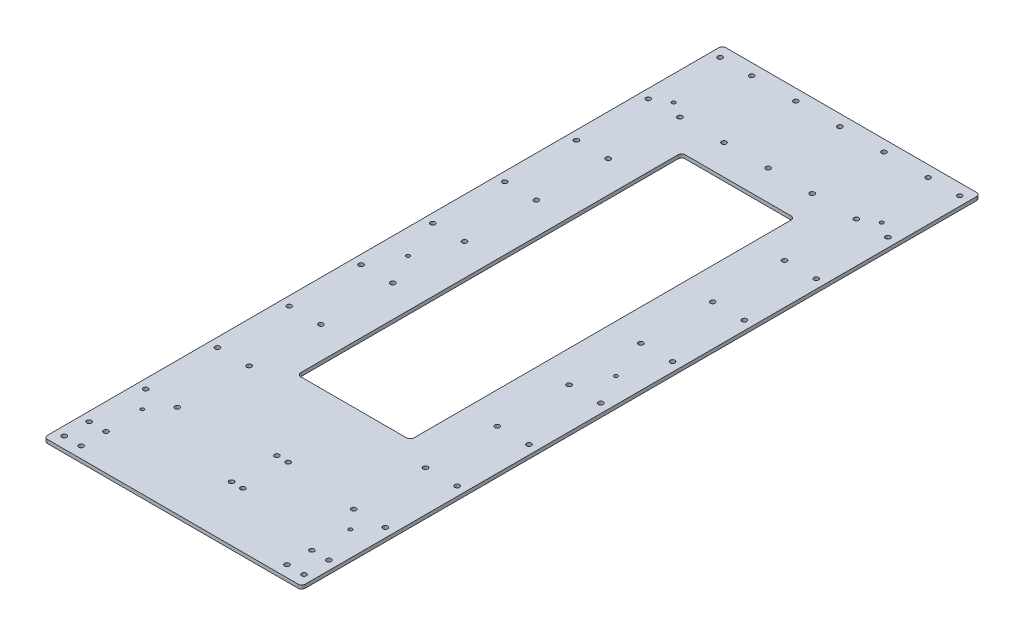
SolidWorks part; units mm, degrees
ref_plane "Front Plane" through (0, 0, 0) normal (0, 0, 1) x (1, 0, 0)
ref_plane "Top Plane" through (0, 0, 0) normal (0, 1, 0) x (1, 0, 0)
ref_plane "Right Plane" through (0, 0, 0) normal (1, 0, 0) x (0, 0, -1)
sketch "Sketch1" plane through (0, 0, 0) normal (0, 1, 0) x (1, 0, 0)
  line L0 (92, 300) -> (92, -300) construction
  line L1 (-114, -300) -> (114, -300)
  line L2 (-114, -300) -> (-114, 300)
  line L3 (-114, 300) -> (114, 300)
  line L4 (114, -300) -> (114, 300)
  line L5 (-114, -300) -> (114, 300) construction
  line L6 (-114, 300) -> (114, -300) construction
  line L7 (-114, 0) -> (114, 0) construction
  line L8 (0, 300) -> (0, -300) construction
  line L9 (78, 290) -> (50, 290) construction
  line L10 (72.9634, -279) -> (112.2482, -279) construction
  line L11 (-50, -140) -> (50, -140)
  line L12 (-50, -140) -> (-50, 200)
  line L13 (-50, 200) -> (50, 200)
  line L14 (50, -140) -> (50, 200)
  line L15 (-24, -231) -> (28.6506, -231) construction
  circle A0 centre (106, 290) radius 2.1
  circle A10 centre (106, -290) radius 2.1
  circle A11 centre (78, -290) radius 2.1 construction
  circle A21 centre (78, 290) radius 2.1
  circle A22 centre (92, 0) radius 1.6
  circle A23 centre (92, 235) radius 1.6
  circle A24 centre (92, -235) radius 1.6
  circle A34 centre (-92, -235) radius 1.6
  circle A42 centre (-78, -290) radius 2.1 construction
  circle A43 centre (-106, -290) radius 2.1
  circle A62 centre (91, -290) radius 2.1
  circle A63 centre (91, -268) radius 2.1
  circle A64 centre (106, -268) radius 2.1
  circle A65 centre (-91, -290) radius 2.1
  circle A66 centre (-106, -268) radius 2.1
  circle A67 centre (-91, -268) radius 2.1
  circle A68 centre (13, -251) radius 2.1
  circle A69 centre (3, -251) radius 2.1
  circle A70 centre (13, -211) radius 2.1
  circle A71 centre (3, -211) radius 2.1
  circle A72 centre (-39, 290) radius 2.1
  circle A73 centre (-39, 226.5) radius 2.1
  circle A74 centre (106, -232) radius 2.1 [skipped]
  circle A75 centre (106, -174) radius 2.1 [skipped]
  circle A76 centre (106, -116) radius 2.1 [skipped]
  circle A77 centre (106, -58) radius 2.1 [skipped]
  circle A78 centre (106, 0) radius 2.1 [skipped]
  circle A79 centre (106, 58) radius 2.1 [skipped]
  circle A80 centre (106, 116) radius 2.1 [skipped]
  circle A81 centre (106, 174) radius 2.1 [skipped]
  circle A82 centre (106, 232) radius 2.1 [skipped]
  circle A83 centre (106, 226.5) radius 2.1
  circle A84 centre (106, 163) radius 2.1
  circle A85 centre (106, 99.5) radius 2.1
  circle A86 centre (106, 36) radius 2.1
  circle A87 centre (106, -27.5) radius 2.1
  circle A88 centre (106, -91) radius 2.1
  circle A89 centre (106, -154.5) radius 2.1
  circle A90 centre (106, -218) radius 2.1
  circle A91 centre (78, 226.5) radius 2.1
  circle A92 centre (78, 163) radius 2.1
  circle A93 centre (78, 99.5) radius 2.1
  circle A94 centre (78, 36) radius 2.1
  circle A95 centre (78, -27.5) radius 2.1
  circle A96 centre (78, -91) radius 2.1
  circle A97 centre (78, -154.5) radius 2.1
  circle A98 centre (78, -218) radius 2.1
  circle A99 centre (-78, -218) radius 2.1
  circle A100 centre (-78, -154.5) radius 2.1
  circle A101 centre (-106, -218) radius 2.1
  circle A102 centre (-106, -154.5) radius 2.1
  circle A103 centre (-78, -91) radius 2.1
  circle A104 centre (-78, -27.5) radius 2.1
  circle A105 centre (-106, -91) radius 2.1
  circle A106 centre (-106, -27.5) radius 2.1
  circle A107 centre (-78, 36) radius 2.1
  circle A108 centre (-78, 99.5) radius 2.1
  circle A109 centre (-106, 36) radius 2.1
  circle A110 centre (-106, 99.5) radius 2.1
  circle A111 centre (-78, 163) radius 2.1
  circle A112 centre (-106, 163) radius 2.1
  circle A113 centre (-78, 226.5) radius 2.1
  circle A114 centre (-106, 226.5) radius 2.1
  circle A115 centre (-92, 235) radius 1.6
  circle A116 centre (-106, 290) radius 2.1
  circle A117 centre (-78, 290) radius 2.1
  circle A118 centre (-92, 0) radius 1.6
  circle A119 centre (0, 290) radius 2.1
  circle A120 centre (0, 226.5) radius 2.1
  circle A121 centre (39, 290) radius 2.1
  circle A122 centre (39, 226.5) radius 2.1
  point P0 (0, 0)
  point P112 (0, 0)
  dimension "D5" = 4.2
  dimension "D8" = 3.2
  dimension "D9" = 3.2
  dimension "D19" = 4.2
  dimension "D23" = 4.2
  dimension "D25" = 4.2
  dimension "D1" = 600
  dimension "D2" = 228
  dimension "D3" = 22
  dimension "D4" = 14
  dimension "D6" = 10
  dimension "D10" = 235
  dimension "D13" = 28
  dimension "D15" = 100
  dimension "D16" = 200
  dimension "D17" = 140
  dimension "D18" = 50
  dimension "D20" = 15
  dimension "D21" = 11
  dimension "D24" = 20
  dimension "D26" = 10
  dimension "D27" = 127
  dimension "D22" = 69
  dimension "D28" = 21
  dimension "D7" = 11
  dimension "D29" = 9
  dimension "D11" = 4
extrude "Boss-Extrude1" add sketch "Sketch1" along normal blind 3.175
fillet "Fillet1" radius 3.2 8 edges at (114, 1.5875, 300) (-114, 1.5875, 300) (-114, 1.5875, -300) (114, 1.5875, -300) (-50, 1.5875, 140) (50, 1.5875, 140) (50, 1.5875, -200) (-50, 1.5875, -200)
equation "\"m4\"= 4.2"
equation "\"m3\"=3.2"
equation "\"D5@Sketch1\"=\"m4\""
equation "\"width\"=228"
equation "\"height\"= 600"
equation "\"D2@Sketch1\"=\"width\""
equation "\"D1@Sketch1\"=\"height\""
equation "\"D8@Sketch1\"=\"m3\""
equation "\"D9@Sketch1\"=\"m3\""
equation "\"D19@Sketch1\"=\"m4\""
equation "\"D23@Sketch1\"=\"m4\""
equation "\"D25@Sketch1\"=\"m4\"'"
